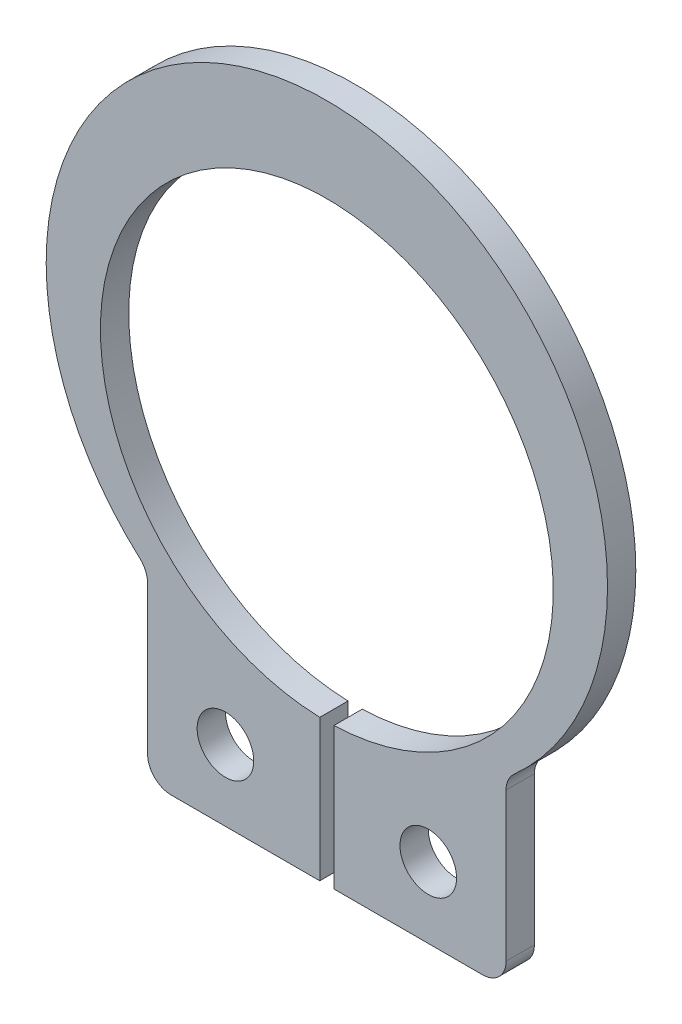
SolidWorks part; units mm, degrees
ref_plane "Front Plane" through (0, 0, 0) normal (0, 0, 1) x (1, 0, 0)
ref_plane "Top Plane" through (0, 0, 0) normal (0, 1, 0) x (1, 0, 0)
ref_plane "Right Plane" through (0, 0, 0) normal (1, 0, 0) x (0, 0, -1)
sketch "Sketch1" plane through (0, 0, 0) normal (0, 0, 1) x (1, 0, 0)
  line L0 (-3.8, -4.1575) -> (-3.8, -7.3)
  line L1 (-3.3, -7.8) -> (-0.15, -7.8)
  line L5 (-0.15, -7.8) -> (-0.15, -4.7977)
  line L6 (0.15, -4.7977) -> (0.15, -7.8)
  line L10 (0.15, -7.8) -> (3.3, -7.8)
  line L11 (3.8, -7.3) -> (3.8, -4.1575)
  line L12 (0, 0) -> (0, 6.6) construction
  arc A0 (3.9667, -3.7849) -> (-3.9667, -3.7849) centre (0, 0.65) ccw
  arc A1 (-3.9667, -3.7849) -> (-3.8, -4.1575) centre (-4.3, -4.1575) cw
  arc A2 (-3.8, -7.3) -> (-3.3, -7.8) centre (-3.3, -7.3) ccw
  arc A4 (-0.15, -4.7977) -> (0.15, -4.7977) centre (0, 0) cw
  arc A6 (3.3, -7.8) -> (3.8, -7.3) centre (3.3, -7.3) ccw
  arc A7 (3.8, -4.1575) -> (3.9667, -3.7849) centre (4.3, -4.1575) cw
  dimension "D1" = 0.3
  dimension "REC_D2_s" = 9.6
  dimension "D2" = 0.5
  dimension "D4" = 0.65
  dimension "REC_MSM_1" = 11.9
  dimension "D3" = 0.5
  dimension "REC_MSM_2" = 7.6
  dimension "REC_A_s" = 3
  dimension "REC_B_s" = 1.8
extrude "Boss-Extrude1" add sketch "Sketch1" against normal blind 0.6
sketch "Sketch2" plane through (0, 0, 0) normal (0, 0, 1) x (1, 0, 0)
  line L0 (-3.8, -6.3) -> (3.8, -6.3) construction
  line L1 (-3.8, -4.1575) -> (-3.8, -7.3) construction
  line L2 (3.8, -7.3) -> (3.8, -4.1575) construction
  line L3 (-3.3, -7.8) -> (-0.15, -7.8) construction
  line L4 (0, 0) -> (0, -7.8) construction
  circle A0 centre (-2.15, -6.3) radius 0.6
  circle A1 centre (2.15, -6.3) radius 0.6
  dimension "REC_D0_s" = 1.2
  dimension "REC_MSM_4" = 1.5
  dimension "REC_MSM_3" = 4.3
extrude "Cut-Extrude1" cut sketch "Sketch2" against normal through all
other "DeleteFace1" [suppressed]
sketch "Sketch3" [suppressed] plane through (0, 0, 0) normal (0, 0, 1) x (1, 0, 0)
  line L0 (-3.8, -6.15) -> (3.8, -6.15) construction
  line L4 (0, 0) -> (0, -7.65) construction
  line L5 (0.15, -7.65) -> (3.3, -7.65) construction
  line L6 (-3.3, -7.65) -> (-0.15, -7.65) construction
  line L7 (-2.15, -5.55) -> (2.15, -5.55)
  line L8 (2.15, -6.75) -> (-2.15, -6.75)
  line L9 (-3.8, -4.3075) -> (-3.8, -7.15) construction
  line L10 (3.8, -7.15) -> (3.8, -4.3075) construction
  arc A0 (-2.15, -5.55) -> (-2.15, -6.75) centre (-2.15, -6.15) ccw
  arc A1 (2.15, -6.75) -> (2.15, -5.55) centre (2.15, -6.15) ccw
  dimension "REC_D0_s" = 1.2
  dimension "REC_MSM_4" = 1.5
  dimension "REC_MSM_3" = 4.3
extrude "Cut-Extrude2" [suppressed] cut sketch "Sketch3" against normal through all
